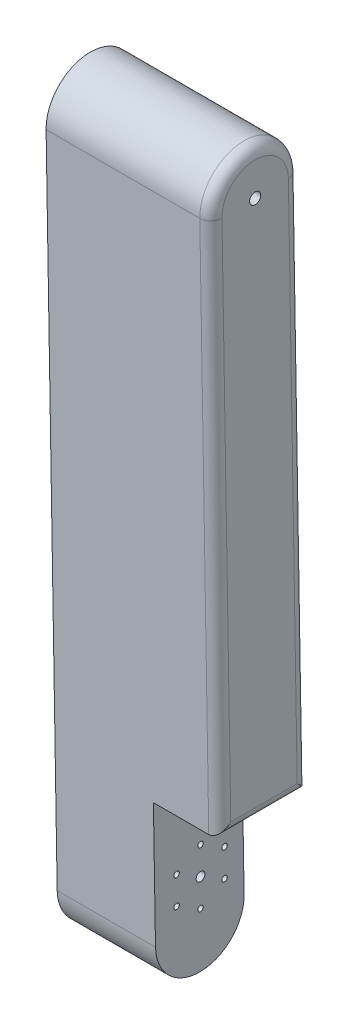
SolidWorks part; units mm, degrees
ref_plane "前视基准面" through (0, 0, 0) normal (0, 0, 1) x (1, 0, 0)
ref_plane "上视基准面" through (0, 0, 0) normal (0, 1, 0) x (1, 0, 0)
ref_plane "右视基准面" through (0, 0, 0) normal (1, 0, 0) x (0, 0, -1)
sketch "草图4" plane through (0, 0, 0) normal (1, 0, 0) x (0, 0, -1)
  line L0 (-19.9972, -0.3333) -> (-14.9972, -300.3333)
  line L1 (0, 0) -> (0.25, -14.9979) construction
  line L2 (19.9972, 0.3333) -> (24.9972, -299.6667)
  line L3 (5.3333, -319.9972) -> (6.3112, -378.6724) construction
  arc A0 (19.9972, 0.3333) -> (-19.9972, -0.3333) centre (0, 0) ccw
  arc A1 (-14.9972, -300.3333) -> (24.9972, -299.6667) centre (5, -300) ccw
  dimension "D2" = 40
  dimension "D1" = 300
extrude "凸台-拉伸3" add sketch "草图4" along normal blind 74.4
sketch "草图5" plane through (0, 0, 0) normal (-1, 0, 0) x (0, 0, 1)
  line L0 (-5.3333, -282.8588) -> (59.606, -282.8588) construction
  line L1 (-5.3333, -319.9972) -> (-5.3333, -89.3538) construction
  arc A0 (-24.9972, -299.6667) -> (14.9972, -300.3333) centre (-5, -300) ccw construction
  circle A1 centre (-5.3333, -282.8588) radius 15.2
  dimension "D1" = 30.4
sketch "草图8" plane through (74.4, 0, 0) normal (1, 0, 0) x (0, 0, -1)
  line L0 (-15.9475, -243.3174) -> (24.0581, -243.3174)
  line L3 (24.0581, -243.3174) -> (24.9972, -299.6667)
  line L5 (-15.9475, -300.3333) -> (-15.9475, -243.3174)
  line L6 (-19.9972, -0.3333) -> (-14.9972, -300.3333) construction
  line L7 (24.9972, -299.6667) -> (19.9972, 0.3333) construction
  arc A0 (-15.9475, -300.3333) -> (24.9972, -299.6667) centre (4.525, -300.0079) ccw
extrude "切除-拉伸1" cut sketch "草图8" against normal blind 30
sketch "草图9" plane through (0, 0.3333, -19.9972) normal (0, 0.0167, -0.9999) x (-1, 0, 0)
  line L5 (-37.2, 20) -> (-37.2, -549.8447) construction
  line L6 (0, 20) -> (-74.4, 20) construction
  line L7 (-62.2, 20) -> (-62.2, -26.4489)
  line L8 (-62.2, -26.4489) -> (-12.2, -26.4489)
  line L9 (-12.2, -26.4489) -> (-12.2, 20)
  line L10 (-12.2, 20) -> (-62.2, 20)
  dimension "D1" = 50
fillet "圆角1" radius 5 4 edges at (74.4, -121.8254, 17.9724) (74.4, 19.9972, 0.3333) (74.4, -121.4921, -22.0276) (74.4, -243.3174, -4.0553)
sketch "草图13" plane through (0, 0, 0) normal (-1, 0, 0) x (0, 0, 1)
  circle A0 centre (-5.3333, -282.8588) radius 12.5 construction
  circle A1 centre (-5.3333, -270.3588) radius 1.25
  circle A2 centre (5.492, -276.6088) radius 1.25
  circle A3 centre (5.492, -289.1088) radius 1.25
  circle A4 centre (-5.3333, -295.3588) radius 1.25
  circle A5 centre (-16.1586, -289.1088) radius 1.25
  circle A6 centre (-16.1586, -276.6088) radius 1.25
  point P18 (-5.3333, -282.8588)
  dimension "D1" = 25
  dimension "D2" = 2.5
  dimension "D3" = 6
extrude "切除-拉伸6" cut sketch "草图13" against normal through all both and the other way through all
sketch "草图14" plane through (0, 0, 0) normal (-1, 0, 0) x (0, 0, 1)
  circle A0 centre (-5.3333, -282.8588) radius 2
  dimension "D1" = 4
extrude "切除-拉伸7" cut sketch "草图14" against normal through all both and the other way through all
sketch "草图15" plane through (0, 0, 0) normal (-1, 0, 0) x (0, 0, 1)
  circle A0 centre (0, 0) radius 2.5
  dimension "D1" = 5
extrude "切除-拉伸8" cut sketch "草图15" against normal blind 100
